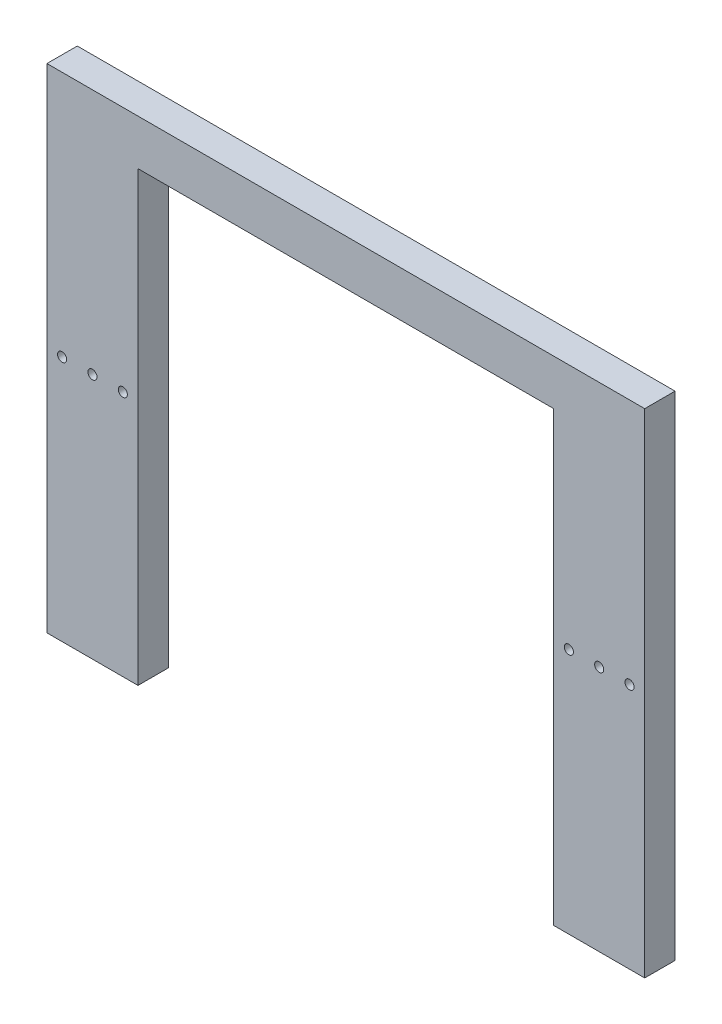
SolidWorks part; units mm, degrees
ref_plane "前视基准面" through (0, 0, 0) normal (0, 0, 1) x (1, 0, 0)
ref_plane "上视基准面" through (0, 0, 0) normal (0, 1, 0) x (1, 0, 0)
ref_plane "右视基准面" through (0, 0, 0) normal (1, 0, 0) x (0, 0, -1)
sketch "草图1" plane through (0, 0, 0) normal (0, 0, 1) x (1, 0, 0)
  line L0 (30, 0) -> (30, -325) construction
  line L1 (0, 0) -> (60, 0)
  line L2 (0, 0) -> (0, -325)
  line L3 (0, -325) -> (60, -325)
  line L4 (60, 0) -> (60, -325)
  line L5 (-274, 0) -> (-334, 0)
  line L6 (-274, 0) -> (-274, -325)
  line L7 (-274, -325) -> (-334, -325)
  line L8 (-334, 0) -> (-334, -325)
  line L9 (-304, 0) -> (-304, -325) construction
  dimension "D1" = 60
  dimension "D2" = 325
  dimension "D3" = 60
  dimension "D4" = 325
  dimension "D5" = 334
extrude "凸台-拉伸1" add sketch "草图1" along normal blind 20
sketch "草图3" plane through (0, 0, 20) normal (0, 0, 1) x (1, 0, 0)
  line L0 (30, 0) -> (30, -325) construction
  line L1 (60, 0) -> (0, 0) construction
  line L2 (0, -325) -> (60, -325) construction
  line L3 (50, 0) -> (50, -325) construction
  line L4 (10, 0) -> (10, -325) construction
  line L5 (60, -325) -> (60, 0) construction
  line L6 (0, 0) -> (0, -325) construction
  line L7 (60, -162.5) -> (0, -162.5) construction
  line L8 (-304, -325) -> (-304, 0) construction
  line L9 (-334, -325) -> (-274, -325) construction
  line L10 (-274, 0) -> (-334, 0) construction
  line L11 (-284, 0) -> (-284, -325) construction
  line L12 (-324, 0) -> (-324, -325) construction
  line L13 (-334, 0) -> (-334, -325) construction
  line L14 (-274, -325) -> (-274, 0) construction
  line L15 (-334, -162.5) -> (-274, -162.5) construction
  circle A0 centre (50, -162.5) radius 3
  circle A1 centre (10, -162.5) radius 3
  circle A2 centre (30, -162.5) radius 3
  circle A3 centre (-324, -162.5) radius 3
  circle A4 centre (-304, -162.5) radius 3
  circle A5 centre (-284, -162.5) radius 3
  point P44 (0, 0)
  dimension "D3" = 6
  dimension "D4" = 6
  dimension "D5" = 6
  dimension "D8" = 6
  dimension "D9" = 6
  dimension "D10" = 6
  dimension "D1" = 10
  dimension "D2" = 10
  dimension "D6" = 10
  dimension "D7" = 10
extrude "切除-拉伸1" cut sketch "草图3" against normal blind 10
sketch "草图5" plane through (0, 0, 20) normal (0, 0, 1) x (1, 0, 0)
  line L0 (0, 0) -> (0, -325) construction
  line L1 (-274, 0) -> (0, 0)
  line L2 (-274, 0) -> (-274, -30)
  line L3 (-274, -30) -> (0, -30)
  line L4 (0, 0) -> (0, -30)
  dimension "D1" = 30
extrude "凸台-拉伸2" add sketch "草图5" against normal up to surface (20 mm away) up to face at (-304, -162.5, 0)
